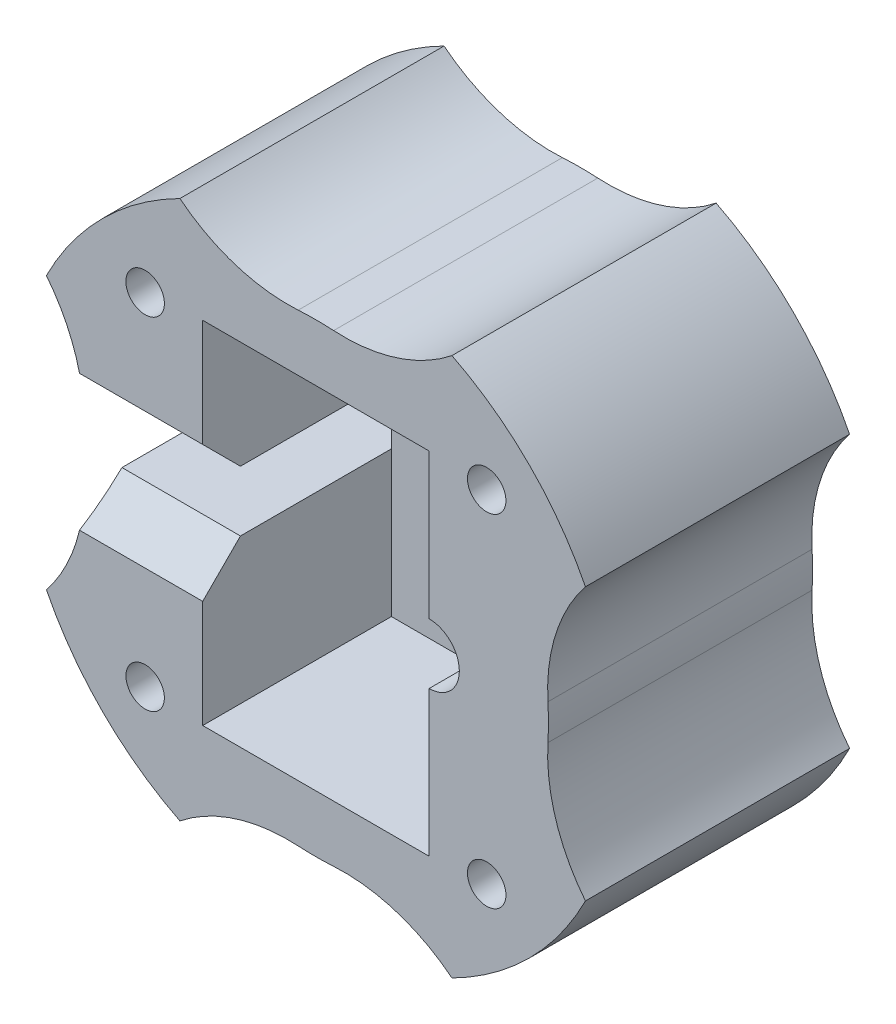
SolidWorks part; units mm, degrees
ref_plane "Front Plane" through (0, 0, 0) normal (0, 0, 1) x (1, 0, 0)
ref_plane "Top Plane" through (0, 0, 0) normal (0, 1, 0) x (1, 0, 0)
ref_plane "Right Plane" through (0, 0, 0) normal (1, 0, 0) x (0, 0, -1)
sketch "Sketch1" plane through (0, 0, 0) normal (0, 0, 1) x (1, 0, 0)
  circle A18 centre (0, 222.5) radius 40
  dimension "D1" = 80
extrude "Boss-Extrude1" add sketch "Sketch1" along normal blind 10
sketch "Sketch3" plane through (0, 0, 10) normal (0, 0, 1) x (1, 0, 0)
  line L1 (15, 245.75) -> (-15, 245.75)
  line L2 (15, 245.75) -> (15, 199.25)
  line L3 (15, 199.25) -> (-15, 199.25)
  line L4 (-15, 245.75) -> (-15, 199.25)
  line L5 (15, 245.75) -> (-15, 199.25) construction
  line L6 (15, 199.25) -> (-15, 245.75) construction
  circle A0 centre (0, 222.5) radius 40 construction
  circle A1 centre (0, 222.5) radius 40
  dimension "D1" = 30
extrude "Boss-Extrude3" add sketch "Sketch3" along normal blind 25
sketch "Sketch4" plane through (0, 0, 35) normal (0, 0, 1) x (1, 0, 0)
  arc A0 (18.0242, 258.209) -> (2.3471, 253.2406) centre (3.6966, 276.2002) cw
  arc A5 (-35.709, 240.5242) -> (-30.7406, 224.8471) centre (-53.7002, 226.1966) cw
  circle A6 centre (0, 222.5) radius 40 construction
  arc A7 (-35.709, 204.4758) -> (-30.7406, 220.1529) centre (-53.7002, 218.8034) ccw
  arc A8 (-35.709, 240.5242) -> (-35.709, 204.4758) centre (0, 222.5) ccw
  arc A9 (35.709, 204.4758) -> (30.7406, 220.1529) centre (53.7002, 218.8034) cw
  arc A10 (35.709, 240.5242) -> (30.7406, 224.8471) centre (53.7002, 226.1966) ccw
  arc A11 (35.709, 204.4758) -> (35.709, 240.5242) centre (0, 222.5) ccw
  arc A12 (30.7406, 220.1529) -> (30.7406, 224.8471) centre (-9.1905, 222.5) ccw
  arc A13 (-30.7406, 220.1529) -> (-30.7406, 224.8471) centre (9.1905, 222.5) cw
  arc A14 (-2.3471, 253.2406) -> (2.3471, 253.2406) centre (0, 213.3095) cw
  arc A15 (-18.0242, 258.209) -> (-2.3471, 253.2406) centre (-3.6966, 276.2002) ccw
  arc A16 (18.0242, 258.209) -> (-18.0242, 258.209) centre (0, 222.5) ccw
  arc A17 (35.709, 204.4758) -> (30.7406, 220.1529) centre (53.7002, 218.8034) cw
  arc A18 (30.7406, 224.8471) -> (30.7406, 220.1529) centre (-9.1905, 222.5) cw
  arc A19 (35.709, 240.5242) -> (30.7406, 224.8471) centre (53.7002, 226.1966) ccw
  arc A20 (35.709, 204.4758) -> (35.709, 240.5242) centre (0, 222.5) ccw
  arc A21 (-18.0242, 186.791) -> (-2.3471, 191.7594) centre (-3.6966, 168.7998) cw
  arc A22 (2.3471, 191.7594) -> (-2.3471, 191.7594) centre (0, 231.6905) cw
  arc A23 (18.0242, 186.791) -> (2.3471, 191.7594) centre (3.6966, 168.7998) ccw
  arc A24 (-18.0242, 186.791) -> (18.0242, 186.791) centre (0, 222.5) ccw
  point P33 (31, 222.5)
  circle M13 centre (0, 222.5) radius 40
  dimension "D4" = 40
  dimension "D5" = 4
extrude "Cut-Extrude1" cut sketch "Sketch4" against normal up to surface (35 mm away) contours A12 A9 A10 M13 | A23 A22 A21 M13 | A16 A15 A14 A0 | A13 A5 A8 A7 up to face at (40, 222.5, 0)
sketch "Sketch5" plane through (0, 0, 35) normal (0, 0, 1) x (1, 0, 0)
  line L0 (-15, 222.5) -> (0, 222.5) construction
  line L1 (-15, 245.75) -> (-15, 199.25) construction
  line L2 (0, 222.5) -> (0, 245.75) construction
  line L3 (15, 245.75) -> (-15, 245.75) construction
  line L4 (0, 222.5) -> (-22.6274, 245.1274) construction
  circle A0 centre (-22.6274, 245.1274) radius 2.55
  circle A1 centre (22.6274, 245.1274) radius 2.55
  circle A2 centre (22.6274, 199.8726) radius 2.55
  circle A3 centre (-22.6274, 199.8726) radius 2.55
  dimension "D3" = 5.1
  dimension "D1" = 45
  dimension "D2" = 32
extrude "Cut-Extrude2" cut sketch "Sketch5" against normal blind 5
sketch "Sketch6" plane through (0, 0, 35) normal (0, 0, 1) x (1, 0, 0)
  line L0 (-15, 222.5) -> (15, 222.5) construction
  line L1 (-15, 245.75) -> (-15, 199.25) construction
  line L2 (15, 199.25) -> (15, 245.75) construction
  line L3 (-15, 222.5) -> (-19, 222.5) construction
  line L4 (-15, 245.75) -> (-15, 199.25) construction
  line L5 (-15, 218.5) -> (-15, 226.5)
  line L6 (0, 245.75) -> (0, 199.25) construction
  line L7 (15, 245.75) -> (-15, 245.75) construction
  line L8 (-15, 199.25) -> (15, 199.25) construction
  line L9 (15, 218.5) -> (15, 226.5)
  arc A0 (-15, 218.5) -> (-15, 226.5) centre (-15, 222.5) cw
  arc A1 (15, 218.5) -> (15, 226.5) centre (15, 222.5) ccw
  dimension "D2" = 4
  dimension "D1" = 4
extrude "Cut-Extrude3" cut sketch "Sketch6" against normal up to surface (25 mm away) up to face at (0, 222.5, 10)
sketch "Sketch8" plane through (-15, 0, 0) normal (1, 0, 0) x (0, 0, -1)
  line L0 (-22, 226.5) -> (-35, 226.5)
  line L1 (-35, 226.5) -> (-35, 218.5)
  line L2 (-22, 226.5) -> (0, 226.5)
  line L3 (-22, 218.5) -> (0, 218.5)
  line L4 (-35, 218.5) -> (-22, 218.5)
  line L9 (0, 224.8471) -> (0, 240.5242) construction
  line L10 (0, 226.5) -> (0, 218.5)
  line L11 (0, 204.4758) -> (0, 220.1529) construction
extrude "Cut-Extrude4" cut sketch "Sketch8" against normal blind 22 contours L2 L10 L3 L4 L1 L0
sketch "Sketch9" plane through (0, 0, 0) normal (0, 0, -1) x (-1, 0, 0)
  line L0 (15, 222.5) -> (0, 222.5) construction
  line L1 (15, 226.5) -> (15, 218.5) construction
  circle A0 centre (0, 222.5) radius 1
  dimension "D1" = 2
extrude "Cut-Extrude5" cut sketch "Sketch9" against normal blind 10
sketch "Sketch10" plane through (0, 0, 0) normal (0, 0, -1) x (-1, 0, 0)
  circle A0 centre (-6, 234.5) radius 1.3
  circle A1 centre (0, 234.5) radius 6 construction
  circle A2 centre (6, 234.5) radius 1.3
  circle A3 centre (6, 210.5) radius 1.3
  circle A4 centre (-6, 210.5) radius 1.3
extrude "Cut-Extrude6" cut sketch "Sketch10" against normal blind 10
chamfer "Chamfer1" distance 5 angle 45 2 edges at (-22.8515, 226.5, 35) (-22.8515, 218.5, 35)
